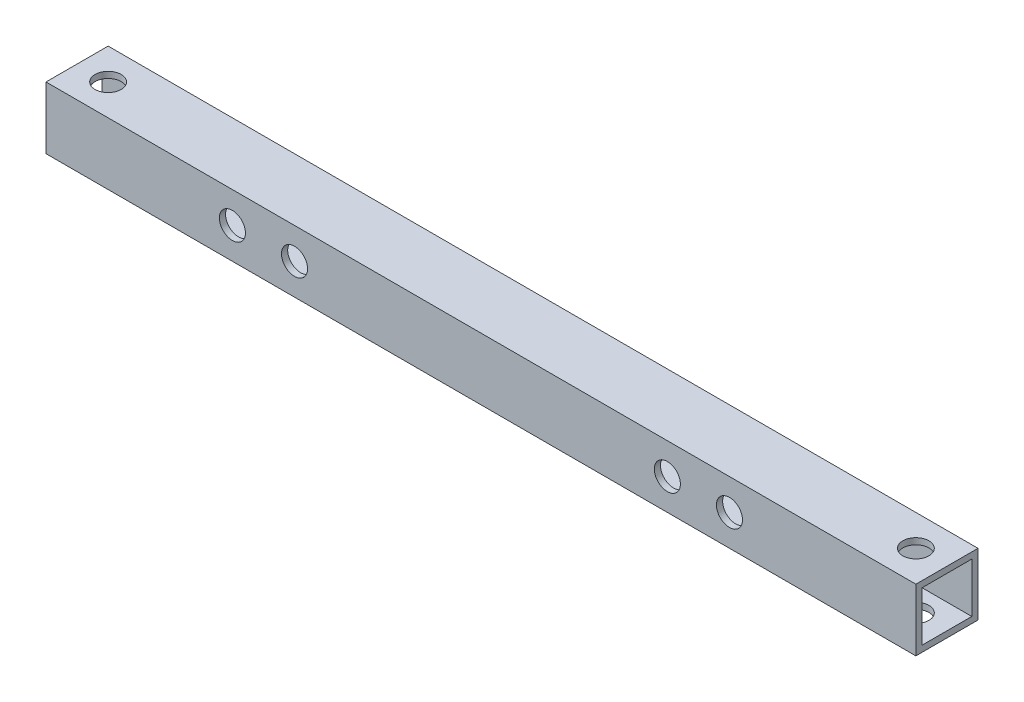
SolidWorks part; units mm, degrees
material "5052-H34"
ref_plane "正面" through (0, 0, 0) normal (0, 0, 1) x (1, 0, 0)
ref_plane "平面" through (0, 0, 0) normal (0, 1, 0) x (1, 0, 0)
ref_plane "右側面" through (0, 0, 0) normal (1, 0, 0) x (0, 0, -1)
sketch "ｽｹｯﾁ1" plane through (0, 0, 0) normal (1, 0, 0) x (0, 0, -1)
  line L1 (-5, 5) -> (5, 5)
  line L2 (-5, 5) -> (-5, -5)
  line L3 (-5, -5) -> (5, -5)
  line L4 (5, 5) -> (5, -5)
  line L5 (-5, 5) -> (5, -5) construction
  line L6 (-5, -5) -> (5, 5) construction
  point P0 (0, 0)
  dimension "D1" = 10
extrude "押し出し-薄板1" add sketch "ｽｹｯﾁ1" along normal blind 140 thin
sketch "ｽｹｯﾁ2" plane through (0, 5, 0) normal (0, 1, 0) x (1, 0, 0)
  line L0 (70, 5) -> (70, -5) construction
  line L1 (140, 5) -> (0, 5) construction
  line L2 (140, -5) -> (0, -5) construction
  line L3 (0, 0) -> (20, 0) construction
  circle A0 centre (20, 0) radius 2.1 construction
  circle A1 centre (5, 0) radius 2.1
  circle A2 centre (135, 0) radius 2.1
  circle A3 centre (120, 0) radius 2.1 construction
  dimension "D1" = 4.2
  dimension "D2" = 5
  dimension "D3" = 15
extrude "ｶｯﾄ - 押し出し1" cut sketch "ｽｹｯﾁ2" against normal through all
sketch "ｽｹｯﾁ3" plane through (0, 0, 5) normal (0, 0, 1) x (1, 0, 0)
  line L0 (70, 5) -> (70, -5) construction
  line L1 (140, 5) -> (0, 5) construction
  line L2 (140, -5) -> (0, -5) construction
  line L3 (0, 0) -> (40, 0) construction
  circle A0 centre (40, 0) radius 2.1
  circle A1 centre (30, 0) radius 2.1
  circle A2 centre (110, 0) radius 2.1
  circle A3 centre (100, 0) radius 2.1
  dimension "D1" = 4.2
  dimension "D2" = 10
  dimension "D3" = 30
extrude "ｶｯﾄ - 押し出し2" cut sketch "ｽｹｯﾁ3" against normal through all
